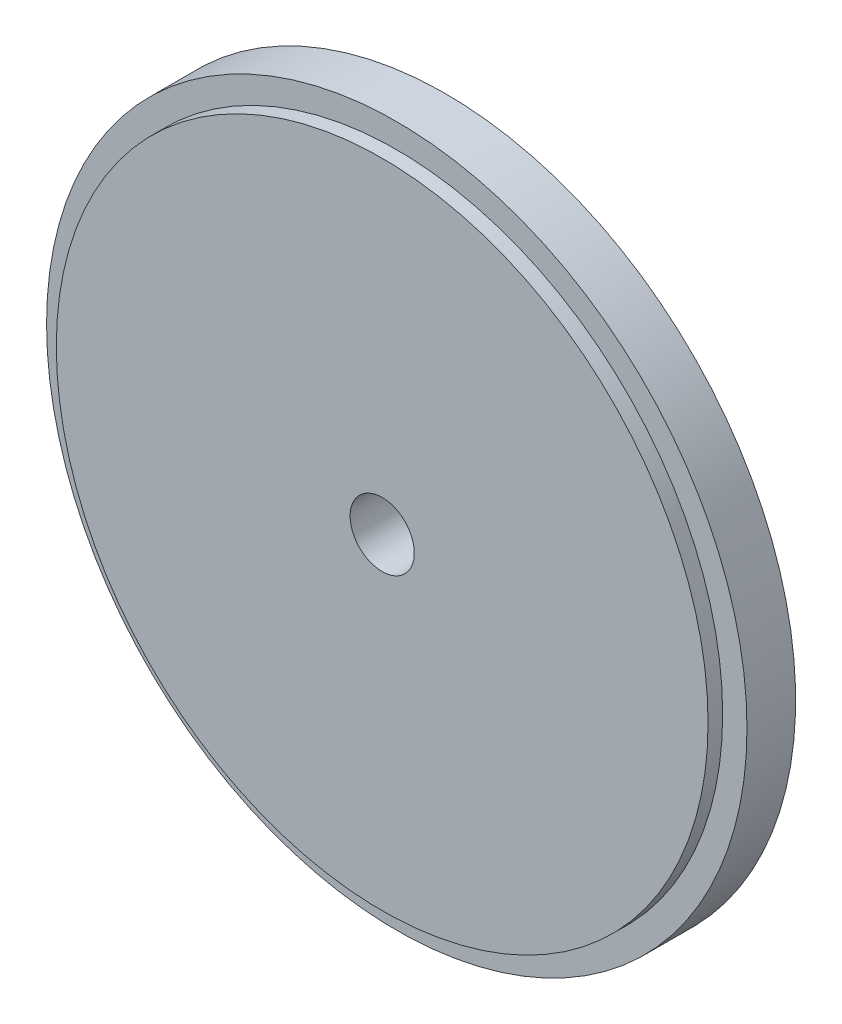
SolidWorks part; units mm, degrees
material "Liga 1060"
ref_plane "Plano frontal" through (0, 0, 0) normal (0, 0, 1) x (1, 0, 0)
ref_plane "Plano superior" through (0, 0, 0) normal (0, 1, 0) x (1, 0, 0)
ref_plane "Plano direito" through (0, 0, 0) normal (1, 0, 0) x (0, 0, -1)
sketch "Esboço1" plane through (0, 0, 0) normal (0, 0, 1) x (1, 0, 0)
  circle A0 centre (0, 0) radius 32.5
  circle A1 centre (0, 0) radius 35
extrude "Ressalto-extrusão1" add sketch "Esboço1" along normal blind 8
sketch "Esboço2" plane through (0, 0, 8) normal (0, 0, 1) x (1, 0, 0)
  circle A0 centre (0, 0) radius 32.5
extrude "Ressalto-extrusão2" add sketch "Esboço2" against normal blind 3
sketch "Esboço3" plane through (0, 0, 8) normal (0, 0, 1) x (1, 0, 0)
  circle A0 centre (0, 0) radius 2.5
extrude "Corte-extrusão1" cut sketch "Esboço3" against normal blind 3
sketch "Esboço4" plane through (0, 0, 5) normal (0, 0, -1) x (-1, 0, 0)
  circle A0 centre (0, 0) radius 37
  circle A1 centre (0, 0) radius 35
extrude "Ressalto-extrusão3" add sketch "Esboço4" against normal through all and the other way through all
sketch "Esboço5" plane through (0, 0, 0) normal (0, 1, 0) x (1, 0, 0)
  line L0 (-37, -1) -> (-37, -7)
  line L1 (-37, -4) -> (-13.2615, -4)
  line L2 (-35.2, -4) -> (-35.2, -1)
  line L3 (-35.2, -1) -> (-37, -1)
  line L4 (-35.2, -4) -> (-35.2, -7)
  line L5 (-35.2, -7) -> (-37, -7)
revolve "Corte-Revolução1" cut sketch "Esboço5" angle 360 about axis through (0, 0, 8) along (0, 0, -1)
sketch "Esboço6" plane through (0, 0, 5) normal (0, 0, -1) x (-1, 0, 0)
  circle A0 centre (0, 0) radius 12.55
  dimension "D1" = 25.1
extrude "Ressalto-extrusão4" add sketch "Esboço6" along normal blind 5
sketch "Esboço7" plane through (0, 0, 0) normal (0, 0, -1) x (-1, 0, 0)
  circle A0 centre (0, 0) radius 7.55
  dimension "D1" = 15.1
extrude "Corte-extrusão2" cut sketch "Esboço7" against normal through all both and the other way through all
sketch "Esboço8" plane through (0, 0, 8) normal (0, 0, 1) x (1, 0, 0)
  circle A0 centre (0, 0) radius 37
  circle A1 centre (0, 0) radius 32.5
  dimension "D1" = 74
extrude "Ressalto-extrusão5" add sketch "Esboço8" against normal up to surface (8 mm away) up to face at (32.5, 0, 0)
sketch "Esboço9" plane through (0, 0, 8) normal (0, 0, 1) x (1, 0, 0)
  circle A0 centre (0, 0) radius 37
  circle A1 centre (0, 0) radius 33.5
extrude "Corte-extrusão8" cut sketch "Esboço9" against normal blind 1.5
sketch "Esboço12" plane through (0, 0, 0) normal (0, 0, -1) x (-1, 0, 0)
  circle A0 centre (0, 0) radius 37
  circle A1 centre (0, 0) radius 33.5
  dimension "D1" = 74
extrude "Corte-extrusão9" cut sketch "Esboço12" against normal blind 1.5
sketch "Esboço13" plane through (0, 0, 1.5) normal (0, 0, -1) x (-1, 0, 0)
  circle A1 centre (0, 0) radius 36
  circle A2 centre (0, 0) radius 37
extrude "Corte-extrusão10" cut sketch "Esboço13" against normal blind 10
sketch "Esboço14" plane through (0, 0, 6.5) normal (0, 0, 1) x (1, 0, 0)
  circle A0 centre (0, 0) radius 37
  circle A1 centre (0, 0) radius 36
  circle A3 centre (0, 0) radius 36
  circle A6 centre (0, 0) radius 36
  circle M3 centre (0, 0) radius 36
  dimension "D1" = 0
extrude "Ressalto-extrusão6" add sketch "Esboço14" against normal up to surface (5 mm away) contours A0 M3 up to face at (-33.5, 0, 1.5)
sketch "Esboço15" plane through (0, 0, 0) normal (0, 0, -1) x (-1, 0, 0)
  circle A0 centre (0, 0) radius 12.55
extrude "Corte-extrusão11" cut sketch "Esboço15" against normal through all
sketch "Esboço16" plane through (0, 0, 5) normal (0, 0, -1) x (-1, 0, 0)
  circle A0 centre (0, 0) radius 12.55 construction
  circle A1 centre (0, 0) radius 12.55
extrude "Ressalto-extrusão7" add sketch "Esboço16" against normal through all
sketch "Esboço17" plane through (0, 0, 5) normal (0, 0, -1) x (-1, 0, 0)
  circle A0 centre (0, 0) radius 10
  dimension "D1" = 20
extrude "Ressalto-extrusão8" add sketch "Esboço17" along normal blind 16
sketch "Esboço18" plane through (0, 0, -11) normal (0, 0, -1) x (-1, 0, 0)
  circle A0 centre (0, 0) radius 3.3
  dimension "D1" = 6.6
extrude "Corte-extrusão12" cut sketch "Esboço18" against normal blind 16
sketch "Esboço19" plane through (0, 0, -11) normal (0, 0, -1) x (-1, 0, 0)
  line L0 (0, -3.3) -> (0, -5.3) construction
  line L1 (-2.975, -5.3) -> (2.975, -5.3)
  line L2 (2.975, -5.3) -> (2.975, -7.95)
  line L3 (2.975, -7.95) -> (-2.975, -7.95)
  line L4 (-2.975, -7.95) -> (-2.975, -5.3)
  line L5 (-3.3, 0) -> (3.3, 0) construction
  line L6 (-2.975, 7.95) -> (-2.975, 5.3)
  line L7 (2.975, 7.95) -> (-2.975, 7.95)
  line L8 (2.975, 5.3) -> (2.975, 7.95)
  line L9 (-2.975, 5.3) -> (2.975, 5.3)
  circle A1 centre (0, 0) radius 3.3 construction
  circle A2 centre (0, 0) radius 3.3 construction
  point P12 (0, -5.3)
  point P19 (0, 5.3)
  dimension "D1" = 2
  dimension "D2" = 5.95
  dimension "D3" = 2.65
extrude "Corte-extrusão13" cut sketch "Esboço19" against normal blind 8
sketch "Esboço21" plane through (0, 5.3, 0) normal (0, 1, 0) x (1, 0, 0)
  line L0 (0, 11) -> (0, 8.5) construction
  line L1 (-2.975, 11) -> (2.975, 11) construction
  circle A0 centre (0, 6.85) radius 1.65
  dimension "D2" = 3.3
  dimension "D1" = 2.5
extrude "Corte-extrusão14" cut sketch "Esboço21" against normal through all both and the other way through all
sketch "Esboço23" plane through (0, 0, 1.5) normal (0, 0, -1) x (-1, 0, 0)
  circle A0 centre (0, 0) radius 36
  circle A1 centre (0, 0) radius 37 construction
  circle A2 centre (0, 0) radius 37
  dimension "D1" = 72
extrude "Corte-extrusão15" cut sketch "Esboço23" against normal through all
sketch "Esboço24" plane through (0, 0, -11) normal (0, 0, -1) x (-1, 0, 0)
  circle A0 centre (0, 0) radius 3.3
extrude "Corte-extrusão16" cut sketch "Esboço24" against normal through all
